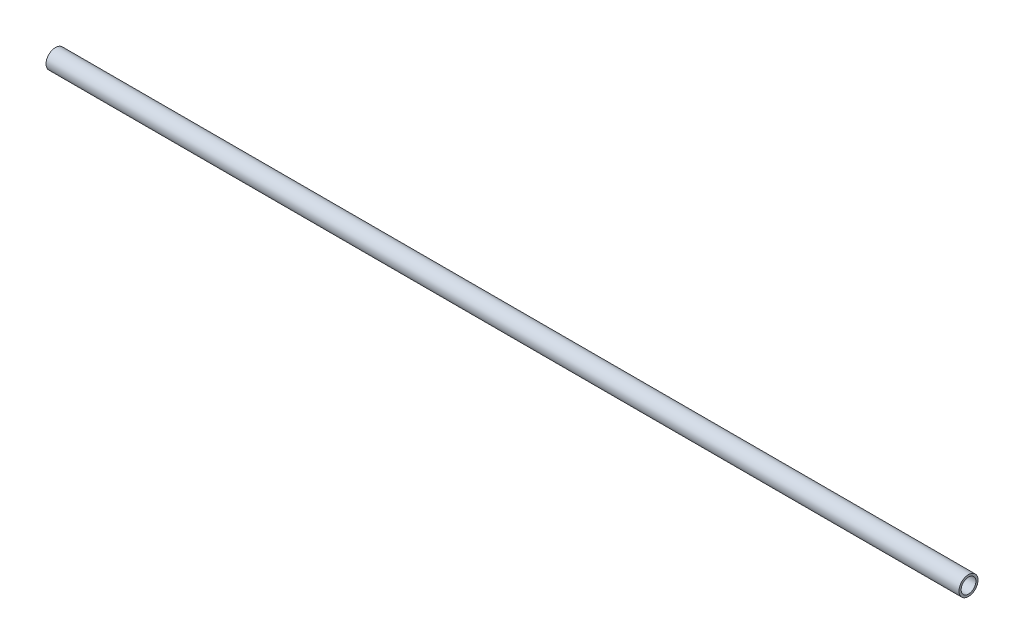
SolidWorks part; units mm, degrees
ref_plane "Front" through (0, 0, 0) normal (0, 0, 1) x (1, 0, 0)
ref_plane "Top" through (0, 0, 0) normal (0, 1, 0) x (1, 0, 0)
ref_plane "Right" through (0, 0, 0) normal (1, 0, 0) x (0, 0, -1)
sketch "Sketch1" plane through (0, 0, 0) normal (1, 0, 0) x (0, 0, -1)
  circle A0 centre (0, 0) radius 3.175
  circle A1 centre (0, 0) radius 2.4638
  point P4 (3.175, 0)
  point P5 (2.4638, 0)
  dimension "OD" = 6.35
  dimension "ID" = 4.9276
  dimension "Wall" = 0.7112
extrude "Extrude1" add sketch "Sketch1" along normal mid plane 304.8
